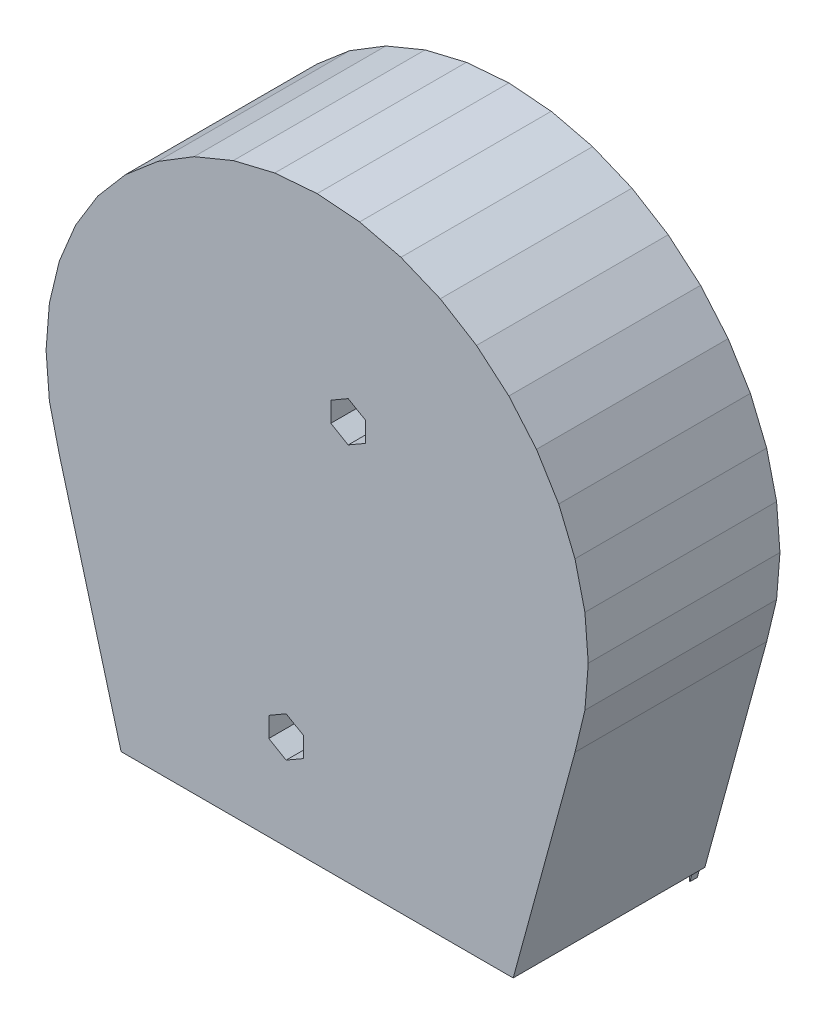
SolidWorks part; units mm, degrees
ref_plane "Front Plane" through (0, 0, 0) normal (0, 0, 1) x (1, 0, 0)
ref_plane "Top Plane" through (0, 0, 0) normal (0, 1, 0) x (1, 0, 0)
ref_plane "Right Plane" through (0, 0, 0) normal (1, 0, 0) x (0, 0, -1)
sketch "Sketch1" plane through (0, 0, 0) normal (0, 0, 1) x (1, 0, 0)
  line L0 (-43.7, 0) -> (-43.162, -6.8362)
  line L1 (-43.162, -6.8362) -> (-41.5612, -13.504)
  line L2 (-41.5612, -13.504) -> (-31.6, -50)
  line L3 (-31.6, -50) -> (31.6, -50)
  line L4 (31.6, -50) -> (41.5612, -13.504)
  line L5 (41.5612, -13.504) -> (43.162, -6.8362)
  line L6 (43.162, -6.8362) -> (43.7, 0)
  line L7 (43.7, 0) -> (43.162, 6.8362)
  line L8 (43.162, 6.8362) -> (41.5612, 13.504)
  line L9 (41.5612, 13.504) -> (38.937, 19.8394)
  line L10 (38.937, 19.8394) -> (35.354, 25.6862)
  line L11 (35.354, 25.6862) -> (30.9006, 30.9006)
  line L12 (30.9006, 30.9006) -> (25.6862, 35.354)
  line L13 (25.6862, 35.354) -> (19.8394, 38.937)
  line L14 (19.8394, 38.937) -> (13.504, 41.5612)
  line L15 (13.504, 41.5612) -> (6.8362, 43.162)
  line L16 (6.8362, 43.162) -> (0, 43.7)
  line L17 (0, 43.7) -> (-6.8362, 43.162)
  line L18 (-6.8362, 43.162) -> (-13.504, 41.5612)
  line L19 (-13.504, 41.5612) -> (-19.8394, 38.937)
  line L20 (-19.8394, 38.937) -> (-25.6862, 35.354)
  line L21 (-25.6862, 35.354) -> (-30.9006, 30.9006)
  line L22 (-30.9006, 30.9006) -> (-35.354, 25.6862)
  line L23 (-35.354, 25.6862) -> (-38.937, 19.8394)
  line L24 (-38.937, 19.8394) -> (-41.5612, 13.504)
  line L25 (-41.5612, 13.504) -> (-43.162, 6.8362)
  line L26 (-43.162, 6.8362) -> (-43.7, 0)
extrude "Boss-Extrude1" add sketch "Sketch1" along normal blind 30.9 from offset 22.3
sketch "Sketch2" plane through (0, 0, 0) normal (0, 0, 1) x (1, 0, 0)
  line L0 (-42.5, 0) -> (-41.9768, -6.6485)
  line L1 (-41.9768, -6.6485) -> (-40.4199, -13.1332)
  line L2 (-40.4199, -13.1332) -> (-30.4, -52)
  line L3 (-30.4, -52) -> (30.4, -52)
  line L4 (30.4, -52) -> (40.4199, -13.1332)
  line L5 (40.4199, -13.1332) -> (41.9768, -6.6485)
  line L6 (41.9768, -6.6485) -> (42.5, 0)
  line L7 (42.5, 0) -> (41.9768, 6.6485)
  line L8 (41.9768, 6.6485) -> (40.4199, 13.1332)
  line L9 (40.4199, 13.1332) -> (37.8678, 19.2946)
  line L10 (37.8678, 19.2946) -> (34.3832, 24.9809)
  line L11 (34.3832, 24.9809) -> (30.052, 30.052)
  line L12 (30.052, 30.052) -> (24.9809, 34.3832)
  line L13 (24.9809, 34.3832) -> (19.2946, 37.8678)
  line L14 (19.2946, 37.8678) -> (13.1332, 40.4199)
  line L15 (13.1332, 40.4199) -> (6.6485, 41.9768)
  line L16 (6.6485, 41.9768) -> (0, 42.5)
  line L17 (0, 42.5) -> (-6.6485, 41.9768)
  line L18 (-6.6485, 41.9768) -> (-13.1332, 40.4199)
  line L19 (-13.1332, 40.4199) -> (-19.2946, 37.8678)
  line L20 (-19.2946, 37.8678) -> (-24.9809, 34.3832)
  line L21 (-24.9809, 34.3832) -> (-30.052, 30.052)
  line L22 (-30.052, 30.052) -> (-34.3832, 24.9809)
  line L23 (-34.3832, 24.9809) -> (-37.8678, 19.2946)
  line L24 (-37.8678, 19.2946) -> (-40.4199, 13.1332)
  line L25 (-40.4199, 13.1332) -> (-41.9768, 6.6485)
  line L26 (-41.9768, 6.6485) -> (-42.5, 0)
extrude "Cut-Extrude1" cut sketch "Sketch2" along normal blind 29.7 from offset 22.3
sketch "Sketch3" plane through (0, 0, 0) normal (0, 0, 1) x (1, 0, 0)
  line L0 (-42.5, 0) -> (-41.9768, -6.6485)
  line L1 (-41.9768, -6.6485) -> (-40.4199, -13.1332)
  line L2 (-40.4199, -13.1332) -> (-30.4, -52)
  line L3 (-30.4, -52) -> (30.4, -52)
  line L4 (30.4, -52) -> (40.4199, -13.1332)
  line L5 (40.4199, -13.1332) -> (41.9768, -6.6485)
  line L6 (41.9768, -6.6485) -> (42.5, 0)
  line L7 (42.5, 0) -> (41.9768, 6.6485)
  line L8 (41.9768, 6.6485) -> (40.4199, 13.1332)
  line L9 (40.4199, 13.1332) -> (37.8678, 19.2946)
  line L10 (37.8678, 19.2946) -> (34.3832, 24.9809)
  line L11 (34.3832, 24.9809) -> (30.052, 30.052)
  line L12 (30.052, 30.052) -> (24.9809, 34.3832)
  line L13 (24.9809, 34.3832) -> (19.2946, 37.8678)
  line L14 (19.2946, 37.8678) -> (13.1332, 40.4199)
  line L15 (13.1332, 40.4199) -> (6.6485, 41.9768)
  line L16 (6.6485, 41.9768) -> (0, 42.5)
  line L17 (0, 42.5) -> (-6.6485, 41.9768)
  line L18 (-6.6485, 41.9768) -> (-13.1332, 40.4199)
  line L19 (-13.1332, 40.4199) -> (-19.2946, 37.8678)
  line L20 (-19.2946, 37.8678) -> (-24.9809, 34.3832)
  line L21 (-24.9809, 34.3832) -> (-30.052, 30.052)
  line L22 (-30.052, 30.052) -> (-34.3832, 24.9809)
  line L23 (-34.3832, 24.9809) -> (-37.8678, 19.2946)
  line L24 (-37.8678, 19.2946) -> (-40.4199, 13.1332)
  line L25 (-40.4199, 13.1332) -> (-41.9768, 6.6485)
  line L26 (-41.9768, 6.6485) -> (-42.5, 0)
extrude "Boss-Extrude2" add sketch "Sketch3" along normal blind 1.2 from offset 22.3
sketch "Sketch4" plane through (0, 0, 0) normal (0, 0, 1) x (1, 0, 0)
  line L0 (-25.3, -53) -> (25.3, -53)
  line L1 (25.3, -53) -> (25.3, 21.3)
  line L2 (25.3, 21.3) -> (-25.3, 21.3)
  line L3 (-25.3, 21.3) -> (-25.3, -53)
extrude "Cut-Extrude2" cut sketch "Sketch4" along normal blind 1.4 from offset 22.2
sketch "Sketch5" plane through (0, 0, 0) normal (0, 0, 1) x (1, 0, 0)
  line L0 (-30.3, -53) -> (30.3, -53)
  line L1 (30.3, -53) -> (30.3, -44.7)
  line L2 (30.3, -44.7) -> (-30.3, -44.7)
  line L3 (-30.3, -44.7) -> (-30.3, -53)
extrude "Cut-Extrude3" cut sketch "Sketch5" along normal blind 1.4 from offset 22.2
sketch "Sketch6" plane through (0, 0, 0) normal (0, 0, 1) x (1, 0, 0)
  circle A0 centre (5, 14.35) radius 3.5
  circle A1 centre (-5, -34.65) radius 3.5
extrude "Boss-Extrude3" add sketch "Sketch6" along normal blind 23 from offset 29
sketch "Sketch7" plane through (0, 0, 0) normal (0, 0, 1) x (1, 0, 0)
  circle A0 centre (5, 14.35) radius 1.725
  circle A1 centre (-5, -34.65) radius 1.725
extrude "Cut-Extrude4" cut sketch "Sketch7" against normal through all and the other way through all
sketch "Sketch8" plane through (0, 0, 0) normal (0, 0, 1) x (1, 0, 0)
  line L0 (7.8, 15.9666) -> (5, 17.5832)
  line L1 (5, 17.5832) -> (2.2, 15.9666)
  line L2 (2.2, 15.9666) -> (2.2, 12.7334)
  line L3 (2.2, 12.7334) -> (5, 11.1168)
  line L4 (5, 11.1168) -> (7.8, 12.7334)
  line L5 (7.8, 12.7334) -> (7.8, 15.9666)
  line L6 (-2.2, -33.0334) -> (-5, -31.4168)
  line L7 (-5, -31.4168) -> (-7.8, -33.0334)
  line L8 (-7.8, -33.0334) -> (-7.8, -36.2666)
  line L9 (-7.8, -36.2666) -> (-5, -37.8832)
  line L10 (-5, -37.8832) -> (-2.2, -36.2666)
  line L11 (-2.2, -36.2666) -> (-2.2, -33.0334)
extrude "Cut-Extrude5" cut sketch "Sketch8" along normal blind 6.1 from offset 47.2
